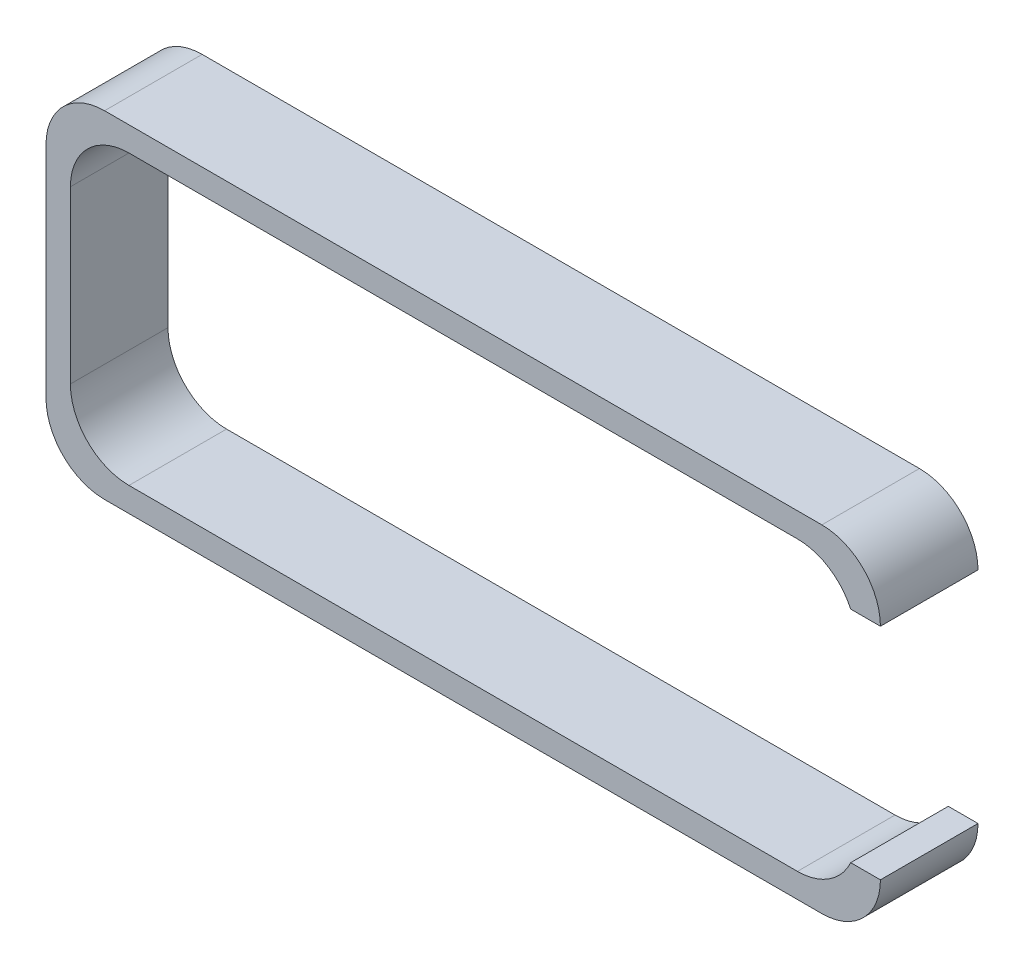
SolidWorks part; units mm, degrees
ref_plane "Plan de face" through (0, 0, 0) normal (0, 0, 1) x (1, 0, 0)
ref_plane "Plan de dessus" through (0, 0, 0) normal (0, 1, 0) x (1, 0, 0)
ref_plane "Plan de droite" through (0, 0, 0) normal (1, 0, 0) x (0, 0, -1)
sketch "Esquisse1" plane through (0, 0, 0) normal (0, 0, 1) x (1, 0, 0)
  line L1 (0, 0) -> (80.5, 0)
  line L2 (0, 0) -> (0, 29.5)
  line L3 (0, 29.5) -> (80.5, 29.5)
  line L4 (80.5, 0) -> (80.5, 29.5)
  line L5 (-2.5, -2.5) -> (83, -2.5)
  line L6 (-2.5, -2.5) -> (-2.5, 32)
  line L7 (-2.5, 32) -> (83, 32)
  line L8 (83, -2.5) -> (83, 32)
  dimension "D1" = 80.5
  dimension "D2" = 29.5
  dimension "D3" = 85.5
  dimension "D4" = 2.5
  dimension "D5" = 34.5
  dimension "D6" = 2.5
extrude "Boss.-Extru.1" add sketch "Esquisse1" along normal blind 10
fillet "Congé1" radius 6 4 edges at (80.5, 0, 5) (80.5, 29.5, 5) (0, 0, 5) (0, 29.5, 5)
fillet "Congé2" radius 6 4 edges at (83, 32, 5) (83, -2.5, 5) (-2.5, -2.5, 5) (-2.5, 32, 5)
sketch "Esquisse3" plane through (83, 0, 0) normal (1, 0, 0) x (0, 0, -1)
  line L1 (0, 26) -> (-10, 26)
  line L2 (0, 26) -> (0, 3.5)
  line L3 (0, 3.5) -> (-10, 3.5)
  line L4 (-10, 26) -> (-10, 3.5)
extrude "Enlèv. mat.-Extru.1" cut sketch "Esquisse3" against normal blind 10
